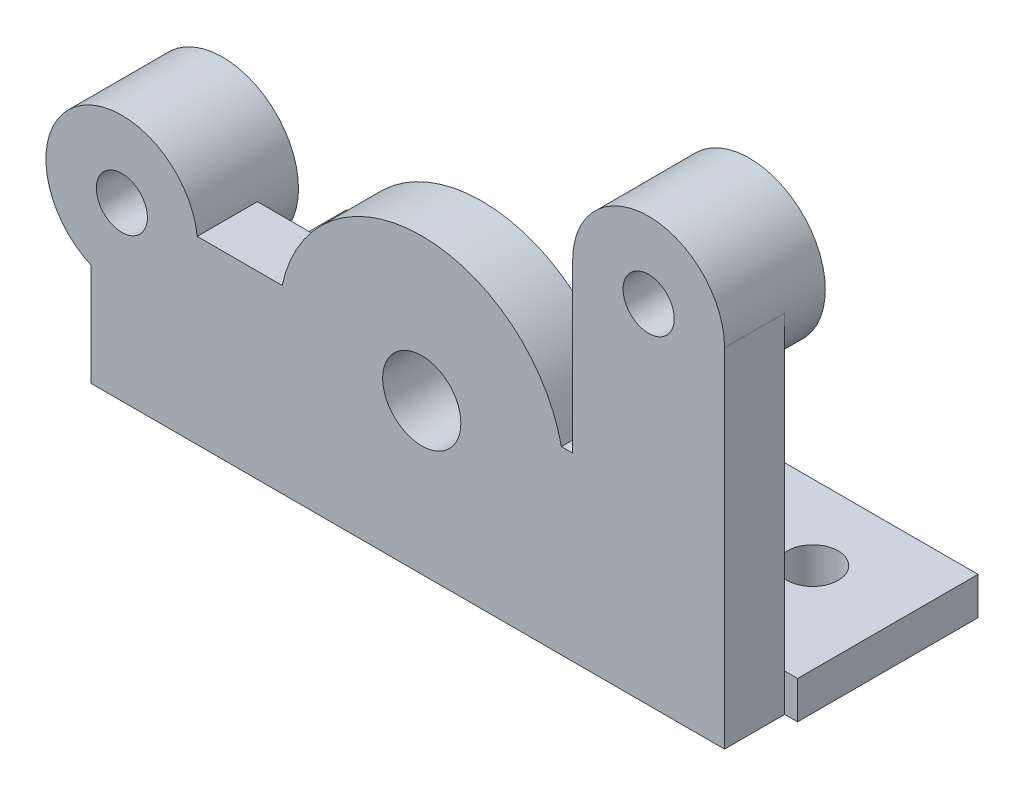
SolidWorks part; units mm, degrees
ref_plane "Front Plane" through (0, 0, 0) normal (0, 0, 1) x (1, 0, 0)
ref_plane "Top Plane" through (0, 0, 0) normal (0, 1, 0) x (1, 0, 0)
ref_plane "Right Plane" through (0, 0, 0) normal (1, 0, 0) x (0, 0, -1)
ref_plane "Plane1" through (0, 0, 343.5) normal (0, 0, 1) x (1, 0, 0)
sketch "Sketch1" plane through (0, 0, 343.5) normal (0, 0, 1) x (1, 0, 0)
  line L0 (278, 30) -> (319, 30)
  line L1 (319, 30) -> (319, 42)
  line L2 (319, 42) -> (278, 42)
  line L3 (278, 42) -> (278, 30)
extrude "Boss-Extrude1" add sketch "Sketch1" along normal blind 4
sketch "Sketch2" plane through (0, 0, 343.5) normal (0, 0, 1) x (1, 0, 0)
  circle A0 centre (300, 40) radius 9.5
  circle A1 centre (300, 40) radius 2.6
extrude "Boss-Extrude2" add sketch "Sketch2" along normal blind 4
sketch "Sketch3" plane through (0, 0, 343.5) normal (0, 0, 1) x (1, 0, 0)
  circle A0 centre (315.0909, 53.1249) radius 5.05
extrude "Boss-Extrude3" add sketch "Sketch3" along normal blind 4
sketch "Sketch4" plane through (0, 0, 343.5) normal (0, 0, 1) x (1, 0, 0)
  circle A0 centre (280.0506, 41.4224) radius 5.05
extrude "Boss-Extrude4" add sketch "Sketch4" along normal blind 4
sketch "Sketch5" plane through (0, 0, 343.5) normal (0, 0, 1) x (1, 0, 0)
  line L0 (310.0409, 30) -> (320.1409, 30)
  line L1 (320.1409, 30) -> (320.1409, 53.1249)
  line L2 (320.1409, 53.1249) -> (310.0409, 53.1249)
  line L3 (310.0409, 53.1249) -> (310.0409, 30)
extrude "Boss-Extrude5" add sketch "Sketch5" along normal blind 4
ref_plane "Plane2" through (0, 30, 0) normal (0, 1, 0) x (1, 0, 0)
sketch "Sketch6" plane through (0, 30, 0) normal (0, 1, 0) x (1, 0, 0)
  line L0 (279, -331.5) -> (321, -331.5)
  line L1 (321, -331.5) -> (321, -343.5)
  line L2 (321, -343.5) -> (279, -343.5)
  line L3 (279, -343.5) -> (279, -331.5)
  circle A0 centre (285, -336.5) radius 1.7
  circle A1 centre (315, -336.5) radius 1.7
extrude "Boss-Extrude6" add sketch "Sketch6" along normal blind 2.5
sketch "Sketch7" plane through (0, 0, 343.5) normal (0, 0, 1) x (1, 0, 0)
  circle A0 centre (300, 40) radius 2.6
extrude "Cut-Extrude1" cut sketch "Sketch7" along normal blind 4
ref_plane "Plane3" through (0, 0, 340.8) normal (0, 0, 1) x (1, 0, 0)
sketch "Sketch8" plane through (0, 0, 340.8) normal (0, 0, 1) x (1, 0, 0)
  circle A0 centre (315.0909, 53.1249) radius 5.05
  circle A1 centre (280.0506, 41.4224) radius 5.05
extrude "Boss-Extrude7" add sketch "Sketch8" along normal blind 2.7
sketch "Sketch9" plane through (0, 0, 340.8) normal (0, 0, 1) x (1, 0, 0)
  circle A0 centre (315.0909, 53.1249) radius 1.7
  circle A1 centre (280.0506, 41.4224) radius 1.7
extrude "Cut-Extrude2" cut sketch "Sketch9" along normal blind 6.7
